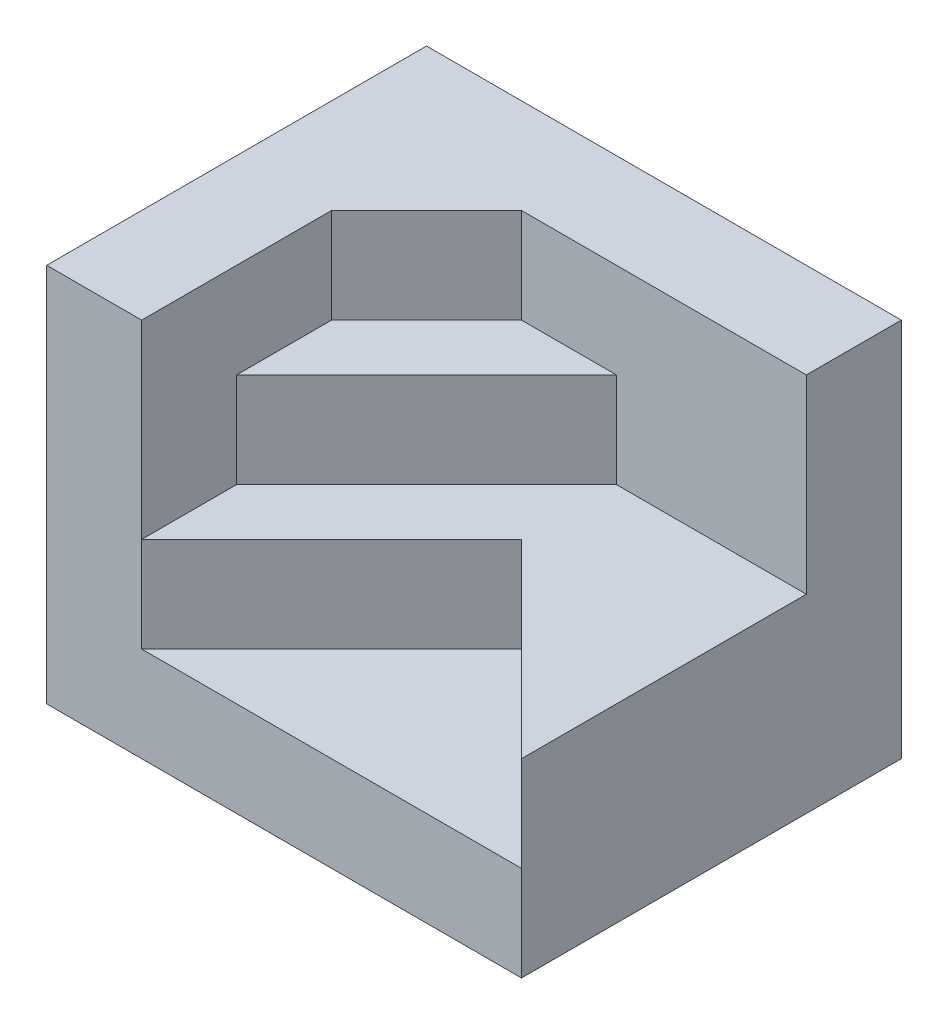
SolidWorks part; units mm, degrees
ref_plane "前基準面" through (0, 0, 0) normal (0, 0, 1) x (1, 0, 0)
ref_plane "上基準面" through (0, 0, 0) normal (0, 1, 0) x (1, 0, 0)
ref_plane "右基準面" through (0, 0, 0) normal (1, 0, 0) x (0, 0, -1)
sketch "草圖1" plane through (0, 0, 0) normal (0, 1, 0) x (1, 0, 0)
  line L0 (0, 0) -> (0, 4)
  line L1 (0, 4) -> (5, 4)
  line L2 (5, 4) -> (5, 0)
  line L3 (5, 0) -> (0, 0)
  dimension "D1" = 4
  dimension "D2" = 5
extrude "填料-伸長1" add sketch "草圖1" along normal blind 1
sketch "草圖2" plane through (0, 1, 0) normal (0, 1, 0) x (1, 0, 0)
  line L0 (0, 0) -> (1, 0)
  line L1 (0, 0) -> (5, 0) construction
  line L2 (1, 0) -> (1, 2)
  line L3 (1, 2) -> (2, 3)
  line L4 (2, 3) -> (5, 3)
  line L5 (5, 0) -> (5, 4) construction
  line L6 (5, 3) -> (5, 4)
  line L7 (5, 4) -> (0, 4)
  line L8 (0, 4) -> (0, 0) construction
  line L9 (5, 4) -> (0, 4) construction
  line L10 (0, 4) -> (0, 0)
  dimension "D1" = 2
  dimension "D2" = 3
  dimension "D3" = 1
  dimension "D4" = 1
extrude "填料-伸長2" add sketch "草圖2" along normal blind 3
sketch "草圖3" plane through (0, 1, 0) normal (0, 1, 0) x (1, 0, 0)
  line L0 (5, 0) -> (3, 2)
  line L1 (3, 2) -> (1, 0)
  line L2 (1, 0) -> (1, 2)
  line L3 (1, 2) -> (2, 3)
  line L4 (2, 3) -> (5, 3)
  line L5 (5, 3) -> (5, 0)
  dimension "D1" = 1
extrude "填料-伸長3" add sketch "草圖3" along normal blind 1
sketch "草圖4" plane through (0, 2, 0) normal (0, 1, 0) x (1, 0, 0)
  line L0 (1, 2) -> (2, 3)
  line L1 (2, 3) -> (3, 3)
  line L2 (5, 3) -> (2, 3) construction
  line L3 (3, 3) -> (1, 1)
  line L4 (1, 2) -> (1, 0) construction
  line L5 (1, 1) -> (1, 2)
  dimension "D1" = 1
extrude "填料-伸長4" add sketch "草圖4" along normal blind 1
